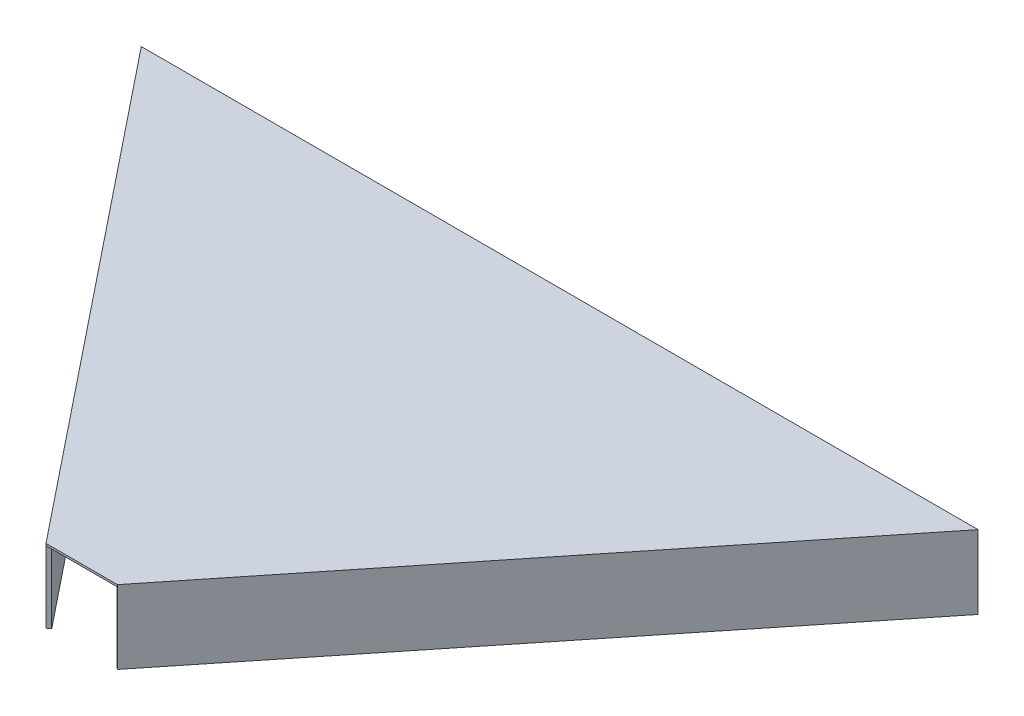
SolidWorks part; units mm, degrees
material "AISI 304"
ref_plane "Front Plane" through (0, 0, 0) normal (0, 0, 1) x (1, 0, 0)
ref_plane "Top Plane" through (0, 0, 0) normal (0, 1, 0) x (1, 0, 0)
ref_plane "Right Plane" through (0, 0, 0) normal (1, 0, 0) x (0, 0, -1)
sketch "Sketch1" plane through (0, 0, 0) normal (0, 1, 0) x (1, 0, 0)
  line L0 (-205, 0) -> (205, 0)
  line L1 (205, 0) -> (17.5, -234.1874)
  line L2 (0, 0) -> (0, 93.1065) construction
  line L3 (-205, 0) -> (-17.5, -234.1874)
  line L4 (200.8367, -2) -> (15.9388, -232.9374)
  line L5 (-200.8367, -2) -> (200.8367, -2)
  line L6 (-200.8367, -2) -> (-15.9388, -232.9374)
  line L7 (15.9388, -232.9374) -> (17.5, -234.1874)
  line L8 (-17.5, -234.1874) -> (-15.9388, -232.9374)
  dimension "D1" = 205
  dimension "D2" = 300
  dimension "D3" = 35
  dimension "D4" = 2
extrude "Boss-Extrude1" add sketch "Sketch1" along normal blind 35
sketch "Sketch2" plane through (0, 35, 0) normal (0, 1, 0) x (1, 0, 0)
  line L0 (205, 0) -> (-205, 0) construction
  line L1 (-200.8367, -2) -> (200.8363, -2)
  line L2 (-200.8367, -2) -> (-200.8367, 0)
  line L3 (-200.8367, 0) -> (200.8363, 0)
  line L4 (200.8363, -2) -> (200.8363, 0)
  line L5 (-200.8367, -2) -> (200.8363, 0) construction
  line L6 (-200.8367, 0) -> (200.8363, -2) construction
  point P4 (-0.0002, -1)
extrude "Cut-Extrude1" cut sketch "Sketch2" against normal through all both and the other way through all
sketch "Sketch3" plane through (0, 35, 0) normal (0, 1, 0) x (1, 0, 0)
  line L0 (-205, 0) -> (-17.5, -234.1874)
  line L1 (-17.5, -234.1874) -> (17.5, -234.1874)
  line L2 (17.5, -234.1874) -> (205, 0)
  line L3 (205, 0) -> (-205, 0)
extrude "Boss-Extrude2" add sketch "Sketch3" along normal blind 1
